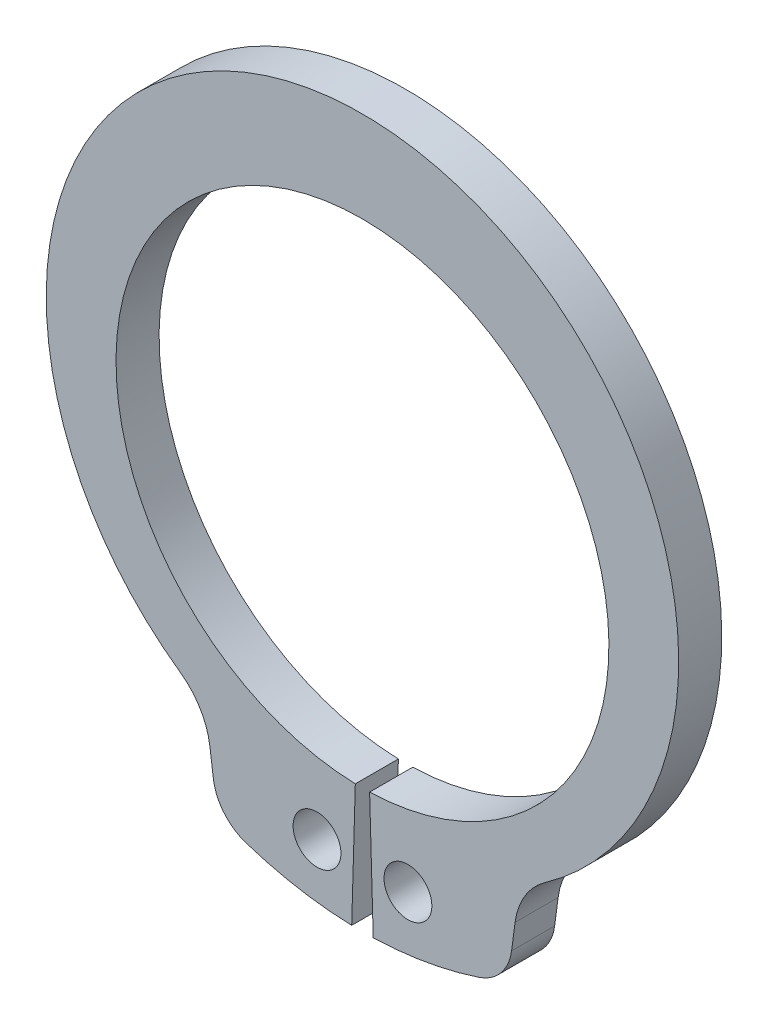
SolidWorks part; units mm, degrees
ref_plane "Plane1" through (0, 0, 0) normal (0, 0, 1) x (1, 0, 0)
ref_plane "Plane2" through (0, 0, 0) normal (0, 1, 0) x (1, 0, 0)
ref_plane "Plane3" through (0, 0, 0) normal (1, 0, 0) x (0, 0, -1)
sketch "Clipboard" plane through (0, 0, 0) normal (0, 0, 1) x (1, 0, 0)
  line L0 (0, 0) -> (1.9, 0)
  line L1 (0, 0) -> (0, 1.1)
  line L2 (0, 0) -> (0, -2.6)
  circle A0 centre (0, 0) radius 0.5
  circle A1 centre (0, 0) radius 5.5
  dimension "HoleDia" = 1
  dimension "ShaftDia" = 11
  dimension "LargeSection" = 1.9
  dimension "SmallSection" = 1.1
  dimension "LugSection" = 2.6
sketch "BodySke" plane through (0, 0, 0) normal (0, 0, 1) x (1, 0, 0)
  line L0 (-1.5431, 0) -> (1.5431, 0) construction
  line L1 (0, 0) -> (0, 7.05) construction
  line L2 (0.1495, -5.1478) -> (0.225, -7.7467)
  line L3 (-0.1495, -5.1478) -> (-0.225, -7.7467)
  line L4 (0, 0) -> (4.6748, -6.1813) construction
  line L5 (0, 0) -> (-4.6748, -6.1813) construction
  line L7 (3.1887, -5.9856) -> (3.116, -6.5375)
  line L8 (-3.1887, -5.9856) -> (-3.116, -6.5375)
  circle A0 centre (0, 0) radius 5.15 construction
  arc A1 (0.1495, -5.1478) -> (-0.1495, -5.1478) centre (0, 0) ccw
  arc A2 (3.77, -4.9849) -> (-3.77, -4.9849) centre (0, 0.442) ccw construction
  arc A3 (0.225, -7.7467) -> (2.4393, -7.3561) centre (0, 0) ccw
  arc A4 (3.8105, -4.9566) -> (3.1887, -5.9856) centre (4.6748, -6.1813) ccw
  arc A5 (-3.1887, -5.9856) -> (-3.8105, -4.9566) centre (-4.6748, -6.1813) ccw
  arc A6 (-2.4393, -7.3561) -> (-0.225, -7.7467) centre (0, 0) ccw
  arc A7 (3.8105, -4.9566) -> (-3.8105, -4.9566) centre (0, 0.442) ccw
  arc A8 (-3.214, -5.7932) -> (3.214, -5.7932) centre (0, 0) ccw construction
  circle A9 centre (0.95, -6.5565) radius 0.5
  circle A10 centre (-0.95, -6.5565) radius 0.5
  arc A11 (3.116, -6.5375) -> (2.4393, -7.3561) centre (2.1246, -6.4069) cw
  arc A12 (-3.116, -6.5375) -> (-2.4393, -7.3561) centre (-2.1246, -6.4069) ccw
  point P28 (3.038, -7.1297)
  point P31 (-3.038, -7.1297)
  dimension "GrooveDia" = 10.3
  dimension "D3" = 1
  dimension "LugRad" = 7.75
  dimension "HoleOffsetRad" = 6.625
  dimension "HoleDia" = 1
  dimension "D2" = 15
  dimension "LargeRad" = 7.05
  dimension "SmallRad" = 6.25
  dimension "Gap" = 0.45
  dimension "SmallAngle" = 74.2
  dimension "HoleSpacing" = 1.9
extrude "Body" add sketch "BodySke" against normal blind 0.9
sketch "NotSke" plane through (0, 0, 0) normal (0, 0, 1) x (1, 0, 0)
  line L0 (0.95, -6.0565) -> (0.95, -7.0565)
  line L1 (0.95, -7.0565) -> (-0.95, -7.0565)
  line L2 (-0.95, -7.0565) -> (-0.95, -6.0565)
  line L3 (-0.95, -6.0565) -> (0.95, -6.0565)
  circle A0 centre (0.95, -6.5565) radius 0.5 construction
  circle A1 centre (-0.95, -6.5565) radius 0.5 construction
extrude "Notch" [suppressed] cut sketch "NotSke" against normal through all
equation "' \"ShaftDia@Clipboard\" = 10"
equation "' \"Thickness@Body\" = 0.9"
equation "' \"GrooveDia@BodySke\" = 9.4"
equation "' \"LugSection@Clipboard\" = 2.6"
equation "' \"LargeSection@Clipboard\" = 1.7"
equation "' \"SmallSection@Clipboard\" = 1.0"
equation "' \"HoleDia@Clipboard\" = 1.0"
equation "' \"ShaftDia@Clipboard\" = 30"
equation "' \"Thickness@Body\" = 2.4"
equation "' \"GrooveDia@BodySke\" = 28.2"
equation "' \"LugSection@Clipboard\" = 5.6"
equation "' \"LargeSection@Clipboard\" = 4.5"
equation "' \"SmallSection@Clipboard\" = 2.5"
equation "' \"HoleDia@Clipboard\" = 2.3"
equation "\"Gap@BodySke\" =  \"Thickness@Body\" / 2"
equation "\"LargeRad@BodySke\" =  \"GrooveDia@BodySke\" / 2 +  \"LargeSection@Clipboard\""
equation "\"SmallRad@BodySke\" =  \"GrooveDia@BodySke\" / 2 +  \"SmallSection@Clipboard\""
equation "\"LugRad@BodySke\" = \"GrooveDia@BodySke\" / 2 + \"LugSection@Clipboard\""
equation "\"HoleOffsetRad@BodySke\" = (  \"ShaftDia@Clipboard\" / 2 + \"LugRad@BodySke\" ) / 2"
equation "\"HoleSpacing@BodySke\" = \"Gap@BodySke\"  * 2 +  \"HoleDia@Clipboard\""
equation "\"HoleDia@BodySke\" =  \"HoleDia@Clipboard\""
equation "\"SmallAngle@BodySke\" = atn(\"HoleSpacing@BodySke\" / 2 / sqr(\"HoleOffsetRad@BodySke\"  * \"HoleOffsetRad@BodySke\" - (\"HoleSpacing@BodySke\" / 2) * (\"HoleSpacing@BodySke\" / 2) ))  * 9 * ( 180 / 3.141593)"
